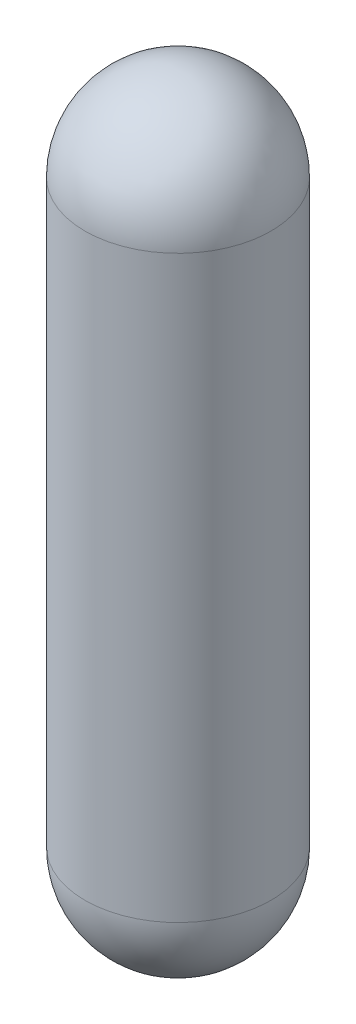
SolidWorks part; units mm, degrees
material "AISI 316, barra ricotta (SS)"
ref_plane "Piano frontale" through (0, 0, 0) normal (0, 0, 1) x (1, 0, 0)
ref_plane "Piano superiore" through (0, 0, 0) normal (0, 1, 0) x (1, 0, 0)
ref_plane "Piano destro" through (0, 0, 0) normal (1, 0, 0) x (0, 0, -1)
sketch "Schizzo1" plane through (0, 0, 0) normal (0, 1, 0) x (1, 0, 0)
  circle A0 centre (0, 0) radius 7
extrude "Estrusione-Estrusione1" add sketch "Schizzo1" along normal blind 43.6
sketch "Schizzo2" plane through (0, 0, 0) normal (0, -1, 0) x (-1, 0, 0)
  line L0 (-0.4157, -6.9876) -> (0.4157, 6.9876)
  arc A0 (-0.4157, -6.9876) -> (0.4157, 6.9876) centre (0, 0) cw
  circle A1 centre (0, 0) radius 7 construction
revolve "Rivoluzione1" add sketch "Schizzo2" angle 180 about L0
sketch "Schizzo3" plane through (0, 43.6, 0) normal (0, 1, 0) x (1, 0, 0)
  line L0 (7, 0) -> (-7, 0)
  arc A0 (-7, 0) -> (7, 0) centre (0, 0) ccw
  circle A1 centre (0, 0) radius 7 construction
revolve "Rivoluzione2" add sketch "Schizzo3" angle 180 about L0
